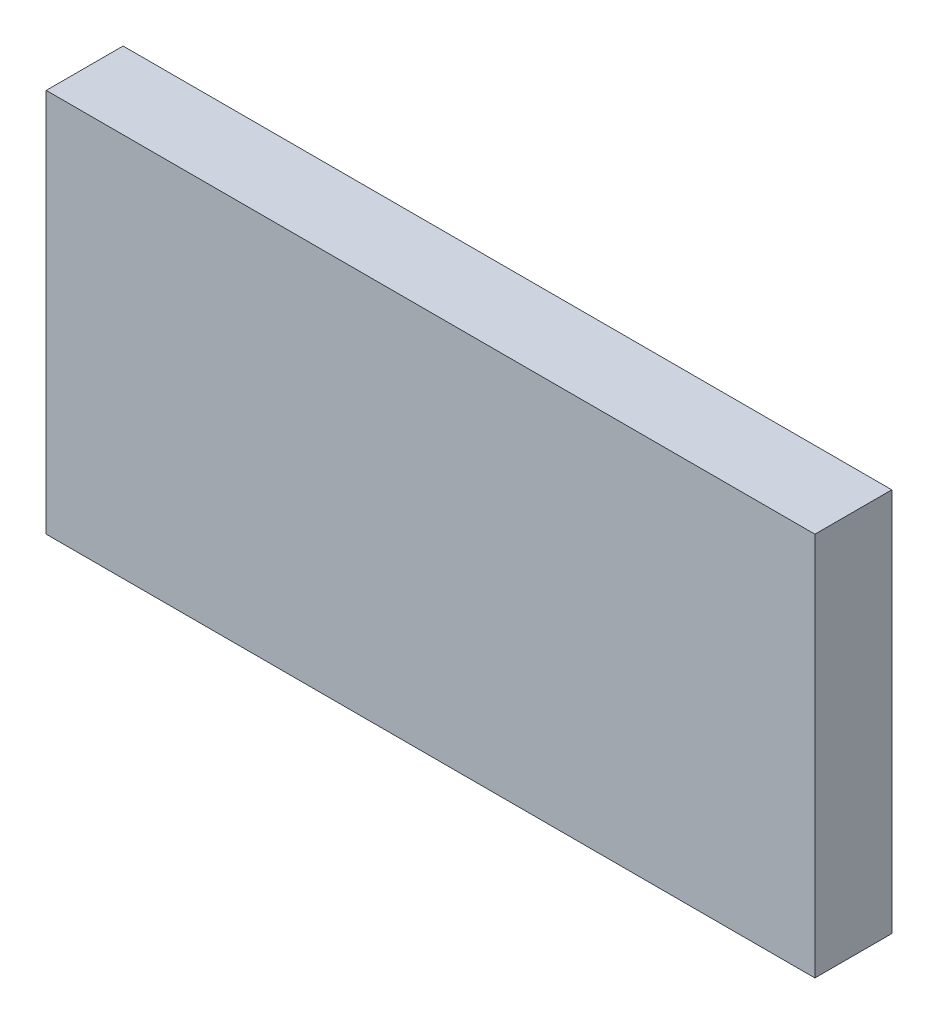
SolidWorks part; units mm, degrees
ref_plane "Front" through (0, 0, 0) normal (0, 0, 1) x (1, 0, 0)
ref_plane "Top" through (0, 0, 0) normal (0, 1, 0) x (1, 0, 0)
ref_plane "Right" through (0, 0, 0) normal (1, 0, 0) x (0, 0, -1)
sketch "Sketch1" plane through (0, 0, 0) normal (0, 0, 1) x (1, 0, 0)
  line L1 (0, 0) -> (-25.4, 0)
  line L2 (0, 0) -> (0, 12.7)
  line L3 (0, 12.7) -> (-25.4, 12.7)
  line L4 (-25.4, 0) -> (-25.4, 12.7)
  dimension "D1" = 25.4
  dimension "D2" = 12.7
extrude "Boss-Extrude1" add sketch "Sketch1" along normal blind 2.54 contours L3 L4 L1 L2
